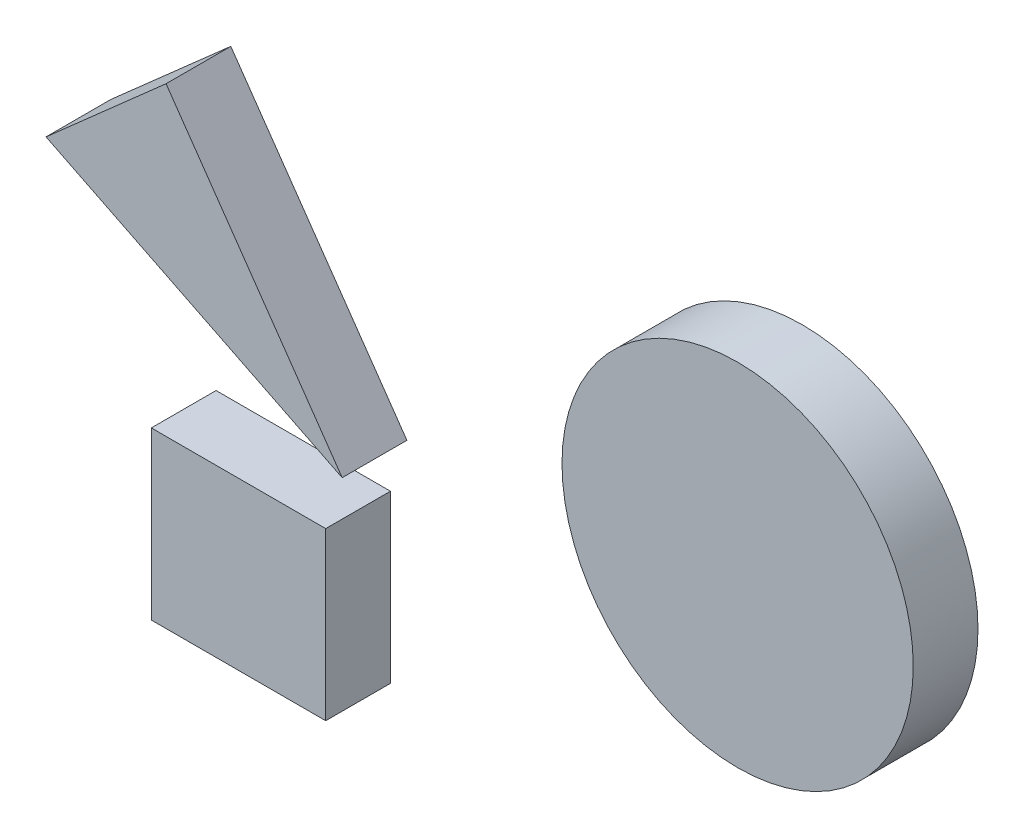
SolidWorks part; units mm, degrees
ref_plane "前视基准面" through (0, 0, 0) normal (0, 0, 1) x (1, 0, 0)
ref_plane "上视基准面" through (0, 0, 0) normal (0, 1, 0) x (1, 0, 0)
ref_plane "右视基准面" through (0, 0, 0) normal (1, 0, 0) x (0, 0, -1)
other "Configuration Table"
sketch "Sketch1" plane through (0, 0, 0) normal (0, 0, 1) x (1, 0, 0)
  circle A0 centre (34.3129, 34.4571) radius 27.1249
extrude "Boss-Extrude1" add sketch "Sketch1" along normal blind 10
sketch "Sketch2" plane through (0, 0, 10) normal (0, 0, 1) x (1, 0, 0)
  line L1 (-46.2358, 17.5092) -> (-19.305, 17.5092)
  line L2 (-46.2358, 17.5092) -> (-46.2358, -8.1932)
  line L3 (-46.2358, -8.1932) -> (-19.305, -8.1932)
  line L4 (-19.305, 17.5092) -> (-19.305, -8.1932)
extrude "Boss-Extrude2" add sketch "Sketch2" along normal blind 10 separate body
sketch "Sketch3" plane through (0, 0, 10) normal (0, 0, 1) x (1, 0, 0)
  line L0 (-43.9604, 64.683) -> (-62.504, 48.3028)
  line L1 (-62.504, 48.3028) -> (-16.7632, 25.587)
  line L2 (-16.7632, 25.587) -> (-43.9604, 64.683)
extrude "Boss-Extrude3" add sketch "Sketch3" along normal blind 10 separate body
